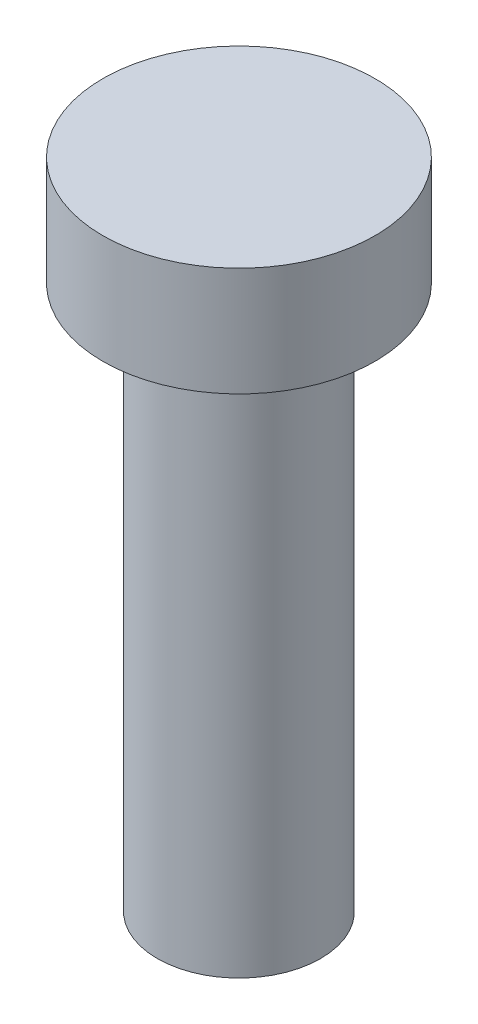
SolidWorks part; units mm, degrees
material "1023 Carbon Steel Sheet (SS)"
ref_plane "Front Plane" through (0, 0, 0) normal (0, 0, 1) x (1, 0, 0)
ref_plane "Top Plane" through (0, 0, 0) normal (0, 1, 0) x (1, 0, 0)
ref_plane "Right Plane" through (0, 0, 0) normal (1, 0, 0) x (0, 0, -1)
sketch "Sketch1" plane through (0, 0, 0) normal (0, 0, 1) x (1, 0, 0)
  line L0 (0, 0) -> (2.25, 0)
  line L1 (55, 0) -> (-55, 0) construction
  line L2 (2.25, 0) -> (2.25, 15)
  line L3 (2.25, 15) -> (3.75, 15)
  line L4 (3.75, 15) -> (3.75, 18)
  line L5 (3.75, 18) -> (0, 18)
  line L6 (0, -55) -> (0, 55) construction
  line L7 (0, 18) -> (0, 0)
  dimension "D1" = 2.25
  dimension "D2" = 15
  dimension "D3" = 3
  dimension "D4" = 3.75
revolve "Revolve1" add sketch "Sketch1" angle 360 about L7
